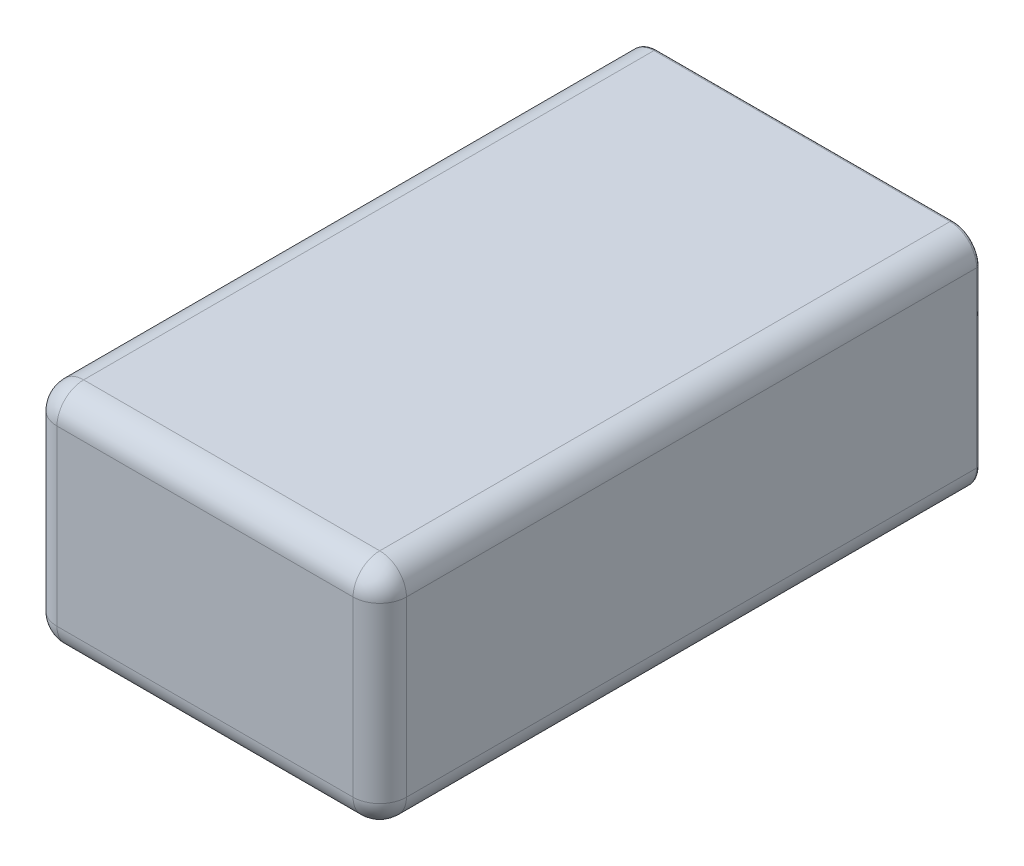
SolidWorks part; units mm, degrees
ref_plane "Plan de face" through (0, 0, 0) normal (0, 0, 1) x (1, 0, 0)
ref_plane "Plan de dessus" through (0, 0, 0) normal (0, 1, 0) x (1, 0, 0)
ref_plane "Plan de droite" through (0, 0, 0) normal (1, 0, 0) x (0, 0, -1)
sketch "Esquisse1" plane through (0, 0, 0) normal (0, 0, 1) x (1, 0, 0)
  line L0 (-16.1614, 0) -> (17.5143, 0) construction
  line L1 (0, 11.454) -> (0, -12.4041) construction
  line L3 (-11.1, 8.5) -> (11.1, 8.5)
  line L4 (-13.1, 6.5) -> (-13.1, -6.5)
  line L5 (-11.1, -8.5) -> (11.1, -8.5)
  line L6 (13.1, 6.5) -> (13.1, -6.5)
  arc A0 (-11.1, 8.5) -> (-13.1, 6.5) centre (-11.1, 6.5) ccw
  arc A1 (11.1, 8.5) -> (13.1, 6.5) centre (11.1, 6.5) cw
  arc A2 (11.1, -8.5) -> (13.1, -6.5) centre (11.1, -6.5) ccw
  arc A3 (-13.1, -6.5) -> (-11.1, -8.5) centre (-11.1, -6.5) ccw
  dimension "D3" = 2
  dimension "D1" = 26.2
  dimension "D2" = 17
extrude "Boss.-Extru.1" add sketch "Esquisse1" along normal blind 45
sketch "Esquisse2" plane through (0, 0, 0) normal (0, 0, -1) x (-1, 0, 0)
  line L24 (11.6, -6.5) -> (11.6, 6.5)
  line L25 (-11.1, -7) -> (11.1, -7)
  line L26 (-11.6, 6.5) -> (-11.6, -6.5)
  line L27 (11.1, 7) -> (-11.1, 7)
  line L28 (11.6, -6.5) -> (11.6, 6.5)
  line L29 (-11.1, -7) -> (11.1, -7)
  line L30 (-11.6, 6.5) -> (-11.6, -6.5)
  line L31 (11.1, 7) -> (-11.1, 7)
  arc A20 (11.6, 6.5) -> (11.1, 7) centre (11.1, 6.5) ccw
  arc A21 (11.1, -7) -> (11.6, -6.5) centre (11.1, -6.5) ccw
  arc A22 (-11.6, -6.5) -> (-11.1, -7) centre (-11.1, -6.5) ccw
  arc A23 (-11.1, 7) -> (-11.6, 6.5) centre (-11.1, 6.5) ccw
  arc A24 (11.6, 6.5) -> (11.1, 7) centre (11.1, 6.5) ccw
  arc A25 (11.1, -7) -> (11.6, -6.5) centre (11.1, -6.5) ccw
  arc A26 (-11.6, -6.5) -> (-11.1, -7) centre (-11.1, -6.5) ccw
  arc A27 (-11.1, 7) -> (-11.6, 6.5) centre (-11.1, 6.5) ccw
  dimension "D1" = 1.5
extrude "Enlèv. mat.-Extru.1" cut sketch "Esquisse2" against normal blind 0.5
fillet "Congé1" radius 0.25 16 edges at (-13.1, 0, 0) (-12.5142, -7.9142, 0) (0, -8.5, 0) (12.5142, -7.9142, 0) (13.1, 0, 0) (12.5142, 7.9142, 0) (0, 8.5, 0) (-12.5142, 7.9142, 0) (11.4536, 6.8536, 0) (11.6, 0, 0) (11.4536, -6.8536, 0) (0, -7, 0) (-11.4536, -6.8536, 0) (-11.6, 0, 0) (-11.4536, 6.8536, 0) (0, 7, 0)
fillet "Congé2" radius 2 8 edges at (0, 8.5, 45) (12.5142, 7.9142, 45) (13.1, 0, 45) (12.5142, -7.9142, 45) (0, -8.5, 45) (-12.5142, -7.9142, 45) (-13.1, 0, 45) (-12.5142, 7.9142, 45)
